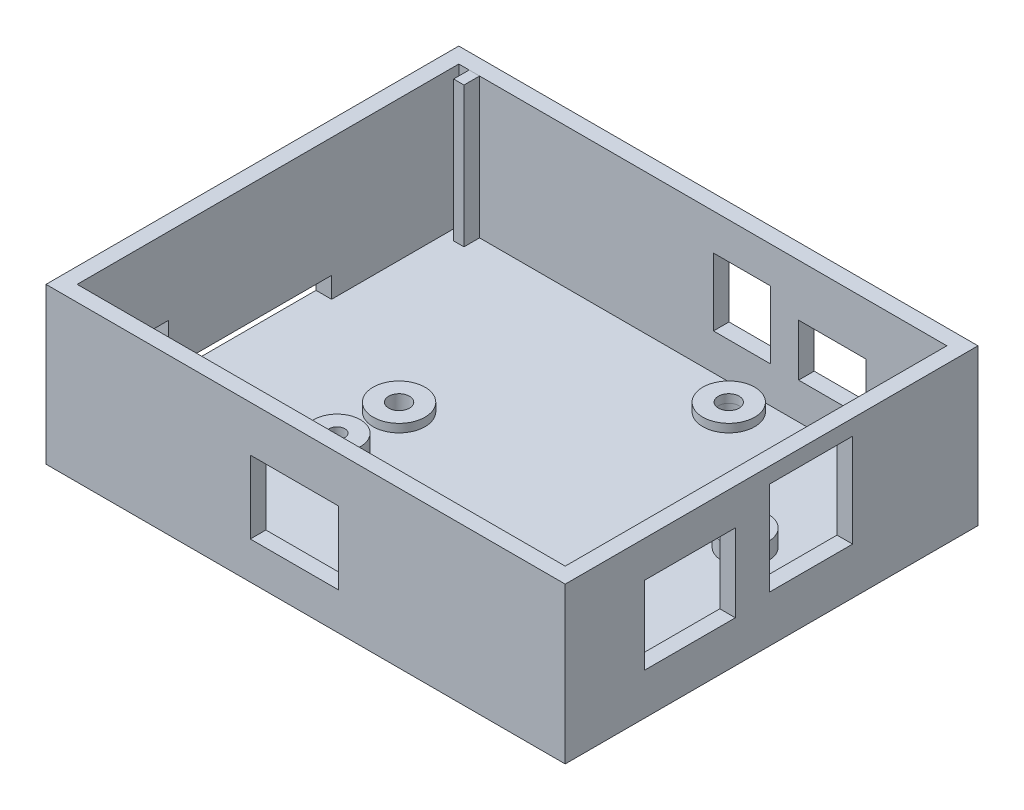
SolidWorks part; units mm, degrees
ref_plane "Front Plane" through (0, 0, 0) normal (0, 0, 1) x (1, 0, 0)
ref_plane "Top Plane" through (0, 0, 0) normal (0, 1, 0) x (1, 0, 0)
ref_plane "Right Plane" through (0, 0, 0) normal (1, 0, 0) x (0, 0, -1)
sketch "Sketch4" plane through (0, 0, 0) normal (0, 1, 0) x (1, 0, 0)
  line L1 (0, 0) -> (100, 0)
  line L2 (0, 0) -> (0, 79.5)
  line L3 (0, 79.5) -> (100, 79.5)
  line L4 (100, 0) -> (100, 79.5)
  dimension "D1" = 79.5
  dimension "D2" = 100
extrude "Boss-Extrude3" add sketch "Sketch4" along normal blind 30
sketch "Sketch5" plane through (0, 30, 0) normal (0, 1, 0) x (1, 0, 0)
  line L8 (3, 76.5) -> (3, 3)
  line L9 (3, 3) -> (97, 3)
  line L10 (97, 3) -> (97, 76.5)
  line L11 (97, 76.5) -> (3, 76.5)
  line L12 (3, 76.5) -> (3, 3)
  line L13 (3, 3) -> (97, 3)
  line L14 (97, 3) -> (97, 76.5)
  line L15 (97, 76.5) -> (3, 76.5)
  dimension "D1" = 3
extrude "Cut-Extrude1" cut sketch "Sketch5" against normal blind 27
sketch "Sketch7" plane through (0, 3, 0) normal (0, 1, 0) x (1, 0, 0)
  line L1 (3.55, 9) -> (96.45, 9)
  line L2 (3.55, 9) -> (3.55, 70.5)
  line L3 (3.55, 70.5) -> (96.45, 70.5)
  line L4 (96.45, 9) -> (96.45, 70.5)
  line L6 (97, 3) -> (97, 76.5) construction
  line L8 (97, 76.5) -> (3, 76.5) construction
  dimension "D1" = 61.5
  dimension "D2" = 92.9
  dimension "D3" = 0.55
  dimension "D4" = 6
sketch "Sketch8" plane through (0, 3, 0) normal (0, 1, 0) x (1, 0, 0)
  line L0 (96.45, 9) -> (96.45, 70.5) construction
  line L1 (3.55, 9) -> (89.15, 9)
  line L2 (3.55, 9) -> (3.55, 63)
  line L3 (3.55, 63) -> (89.15, 63)
  line L4 (89.15, 9) -> (89.15, 63)
  line L5 (3.55, 70.5) -> (96.45, 70.5) construction
  dimension "D1" = 54
  dimension "D2" = 85.6
  dimension "D3" = 7.3
  dimension "D4" = 7.5
sketch "Sketch9" plane through (0, 3, 0) normal (0, 1, 0) x (1, 0, 0)
  line L0 (0, 79.5) -> (0, 0) construction
  line L2 (3, 3) -> (97, 3) construction
  circle A0 centre (60, 8) radius 5
  circle A1 centre (60, 71.5) radius 5
  dimension "D1" = 10
  dimension "D2" = 10
  dimension "D6" = 5
  dimension "D3" = 60
  dimension "D4" = 60
  dimension "D5" = 63.5
extrude "Boss-Extrude5" add sketch "Sketch9" along normal blind 1.6 separate body
sketch "Sketch10" plane through (0, 4.6, 0) normal (0, 1, 0) x (1, 0, 0)
  circle A2 centre (60, 71.5) radius 2
  circle A3 centre (60, 71.5) radius 2
  dimension "D1" = 3
extrude "Cut-Extrude2" cut sketch "Sketch10" against normal through all
sketch "Sketch11" plane through (0, 4.6, 0) normal (0, 1, 0) x (1, 0, 0)
  circle A2 centre (60, 8) radius 2
  circle A3 centre (60, 8) radius 2
  dimension "D1" = 3
extrude "Cut-Extrude3" cut sketch "Sketch11" against normal through all
sketch "Sketch12" plane through (0, 3, 0) normal (0, 1, 0) x (1, 0, 0)
  line L0 (3.55, 9) -> (3.55, 70.5) construction
  line L1 (3.55, 9) -> (96.45, 9) construction
  line L2 (89.15, 9) -> (89.15, 63) construction
  line L3 (3.55, 63) -> (89.15, 63) construction
  circle A0 centre (29.05, 27) radius 4.5
  circle A1 centre (84.15, 50.5) radius 4.5
  dimension "D1" = 9
  dimension "D2" = 9
  dimension "D3" = 25.5
  dimension "D4" = 18
  dimension "D5" = 5
  dimension "D6" = 12.5
extrude "Boss-Extrude6" add sketch "Sketch12" along normal blind 3.2
sketch "Sketch13" plane through (0, 6.2, 0) normal (0, 1, 0) x (1, 0, 0)
  circle A2 centre (29.05, 27) radius 1.5
  circle A3 centre (29.05, 27) radius 1.5
  dimension "D1" = 3
extrude "Cut-Extrude4" cut sketch "Sketch13" against normal through all
sketch "Sketch14" plane through (0, 6.2, 0) normal (0, 1, 0) x (1, 0, 0)
  circle A2 centre (84.15, 50.5) radius 1.5
  circle A3 centre (84.15, 50.5) radius 1.5
  dimension "D1" = 3
extrude "Cut-Extrude5" cut sketch "Sketch14" against normal through all
sketch "Sketch15" plane through (0, 3, 0) normal (0, 1, 0) x (1, 0, 0)
  line L0 (97, 76.5) -> (3, 76.5) construction
  line L1 (5, 76.5) -> (7, 76.5)
  line L2 (5, 76.5) -> (5, 73.5)
  line L3 (5, 73.5) -> (7, 73.5)
  line L4 (7, 76.5) -> (7, 73.5)
  line L5 (3, 76.5) -> (3, 3) construction
  dimension "D1" = 2
  dimension "D2" = 3
  dimension "D3" = 2
extrude "Boss-Extrude7" add sketch "Sketch15" along normal blind 27 separate body
sketch "Sketch17" plane through (3, 0, 0) normal (1, 0, 0) x (0, 0, -1)
  line L0 (76.5, 3) -> (3, 3) construction
  line L1 (24, 3) -> (52, 3)
  line L2 (24, 3) -> (24, 7)
  line L3 (24, 7) -> (52, 7)
  line L4 (52, 3) -> (52, 7)
  dimension "D1" = 4
  dimension "D2" = 28
  dimension "D3" = 15
  dimension "D4" = 11
extrude "Cut-Extrude8" cut sketch "Sketch17" against normal blind 22.2
sketch "Sketch18" plane through (3, 0, 0) normal (1, 0, 0) x (0, 0, -1)
  line L1 (12.55, 7.2) -> (20.55, 7.2)
  line L2 (12.55, 7.2) -> (12.55, 15.2)
  line L3 (12.55, 15.2) -> (20.55, 15.2)
  line L4 (20.55, 7.2) -> (20.55, 15.2)
  line L5 (9, 3) -> (70.5, 3) construction
  dimension "D1" = 8
  dimension "D2" = 8
  dimension "D3" = 3.55
  dimension "D4" = 42.45
  dimension "D5" = 4.2
extrude "Cut-Extrude9" cut sketch "Sketch18" against normal blind 22.2
sketch "Sketch19" plane through (0, 0, -3) normal (0, 0, -1) x (-1, 0, 0)
  line L0 (-3, 3) -> (-97, 3) construction
  line L1 (-56.35, 21.2) -> (-39.35, 21.2)
  line L2 (-56.35, 21.2) -> (-56.35, 7.2)
  line L3 (-56.35, 7.2) -> (-39.35, 7.2)
  line L4 (-39.35, 21.2) -> (-39.35, 7.2)
  dimension "D1" = 35.8
  dimension "D2" = 17
  dimension "D3" = 32.8
  dimension "D4" = 4.2
  dimension "D5" = 14
extrude "Cut-Extrude11" cut sketch "Sketch19" against normal blind 22.2 contours L2 L3 L4 L1
sketch "Sketch20" plane through (0, 3, 0) normal (0, 1, 0) x (1, 0, 0)
  circle A0 centre (28.2518, 39.75) radius 5
  circle A1 centre (60, 8) radius 5 construction
  circle A2 centre (60, 71.5) radius 2 construction
  dimension "D1" = 10
  dimension "D2" = 44.9
  dimension "D3" = 44.9
extrude "Boss-Extrude8" add sketch "Sketch20" along normal blind 1.6
sketch "Sketch21" plane through (0, 4.6, 0) normal (0, 1, 0) x (1, 0, 0)
  circle A2 centre (28.2518, 39.75) radius 2
  circle A3 centre (28.2518, 39.75) radius 2
  dimension "D1" = 3
extrude "Cut-Extrude12" cut sketch "Sketch21" against normal through all
sketch "Sketch22" plane through (0, 0, 0) normal (0, -1, 0) x (-1, 0, 0)
  line L0 (-60, 8) -> (-60, 71.5)
  line L1 (-28.2518, 39.75) -> (-60, 39.75)
  dimension "D1" = 31.7482
  dimension "D2" = 63.5
sketch "Sketch23" plane through (0, 0, -76.5) normal (0, 0, 1) x (1, 0, 0)
  line L0 (3.55, 3) -> (96.45, 3) construction
  line L1 (68.45, 10) -> (81.45, 10)
  line L2 (68.45, 10) -> (68.45, 20)
  line L3 (68.45, 20) -> (81.45, 20)
  line L4 (81.45, 10) -> (81.45, 20)
  line L5 (52.05, 10) -> (63.05, 10)
  line L6 (52.05, 10) -> (52.05, 23)
  line L7 (52.05, 23) -> (63.05, 23)
  line L8 (63.05, 10) -> (63.05, 23)
  dimension "D1" = 17
  dimension "D2" = 20
  dimension "D3" = 15
  dimension "D4" = 13
  dimension "D5" = 10
  dimension "D6" = 11
  dimension "D7" = 5.4
  dimension "D8" = 13
extrude "Cut-Extrude13" cut sketch "Sketch23" against normal through all
sketch "Sketch24" plane through (97, 0, 0) normal (-1, 0, 0) x (0, 0, 1)
  line L0 (-9, 3) -> (-70.5, 3) construction
  line L1 (-55.3478, 9) -> (-39.3478, 9)
  line L2 (-55.3478, 9) -> (-55.3478, 27)
  line L3 (-55.3478, 27) -> (-39.3478, 27)
  line L4 (-39.3478, 9) -> (-39.3478, 27)
  line L5 (-32.7672, 8) -> (-15.2466, 8)
  line L6 (-32.7672, 8) -> (-32.7672, 23)
  line L7 (-32.7672, 23) -> (-15.2466, 23)
  line L8 (-15.2466, 8) -> (-15.2466, 23)
  dimension "D1" = 16
  dimension "D2" = 18
  dimension "D3" = 24
  dimension "D4" = 15
  dimension "D5" = 20
extrude "Cut-Extrude15" cut sketch "Sketch24" against normal through all
